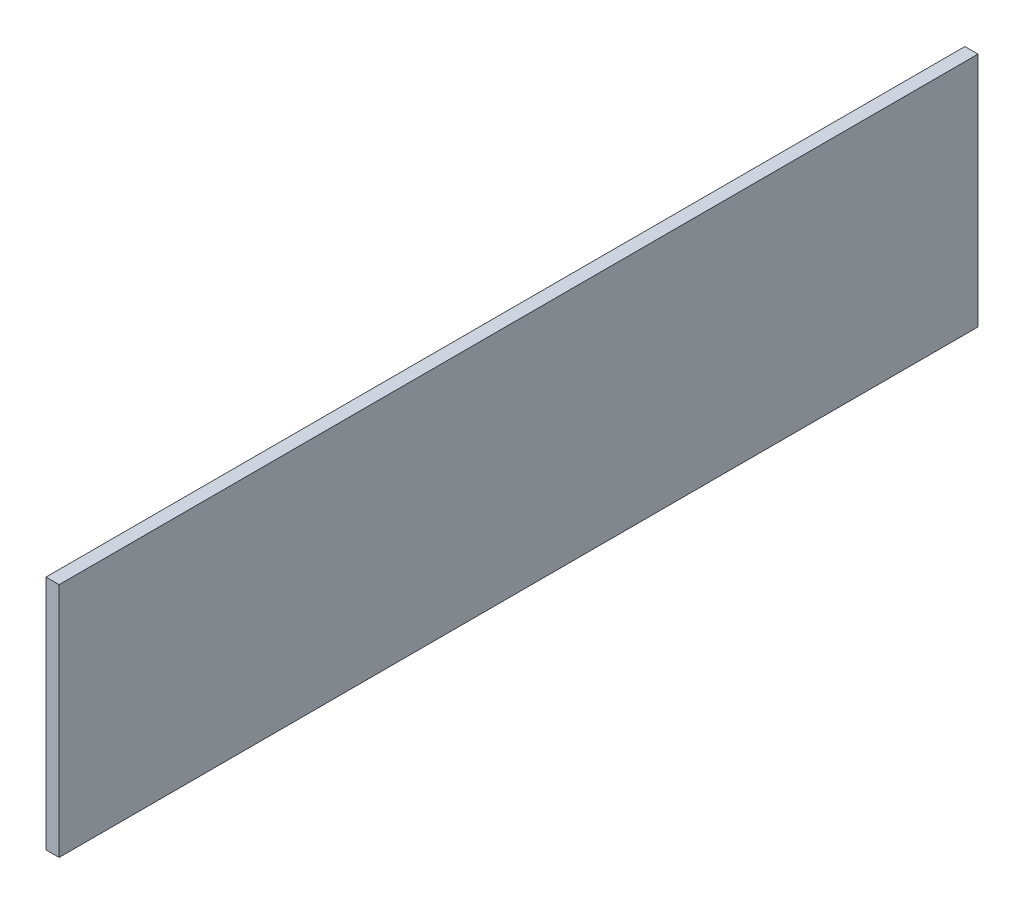
SolidWorks part; units mm, degrees
ref_plane "Front Plane" through (0, 0, 0) normal (0, 0, 1) x (1, 0, 0)
ref_plane "Top Plane" through (0, 0, 0) normal (0, 1, 0) x (1, 0, 0)
ref_plane "Right Plane" through (0, 0, 0) normal (1, 0, 0) x (0, 0, -1)
sketch "Sketch2" plane through (0, 0, 0) normal (1, 0, 0) x (0, 0, -1)
  line L1 (0, 0) -> (70, 0)
  line L2 (0, 0) -> (0, 18)
  line L3 (0, 18) -> (70, 18)
  line L4 (70, 0) -> (70, 18)
  dimension "D1" = 70
  dimension "D2" = 18
extrude "Boss-Extrude1" add sketch "Sketch2" along normal blind 1
